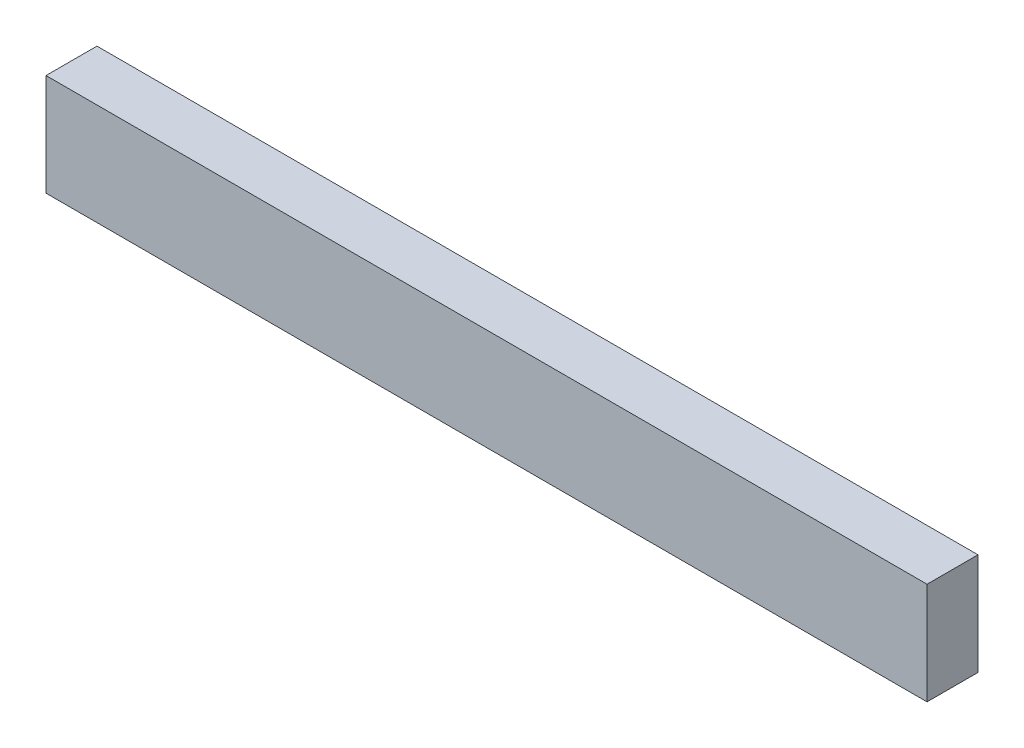
SolidWorks part; units mm, degrees
material "Sapin"
ref_plane "Plan de face" through (0, 0, 0) normal (0, 0, 1) x (1, 0, 0)
ref_plane "Plan de dessus" through (0, 0, 0) normal (0, 1, 0) x (1, 0, 0)
ref_plane "Plan de droite" through (0, 0, 0) normal (1, 0, 0) x (0, 0, -1)
sketch "Esquisse1" plane through (0, 0, 0) normal (0, 0, 1) x (1, 0, 0)
  line L1 (-207.5, -24) -> (207.5, -24)
  line L2 (-207.5, -24) -> (-207.5, 24)
  line L3 (-207.5, 24) -> (207.5, 24)
  line L4 (207.5, -24) -> (207.5, 24)
  line L5 (-207.5, -24) -> (207.5, 24) construction
  line L6 (-207.5, 24) -> (207.5, -24) construction
  point P0 (0, 0)
  dimension "D1" = 48
  dimension "D2" = 415
extrude "Boss.-Extru.1" add sketch "Esquisse1" along normal mid plane 24
